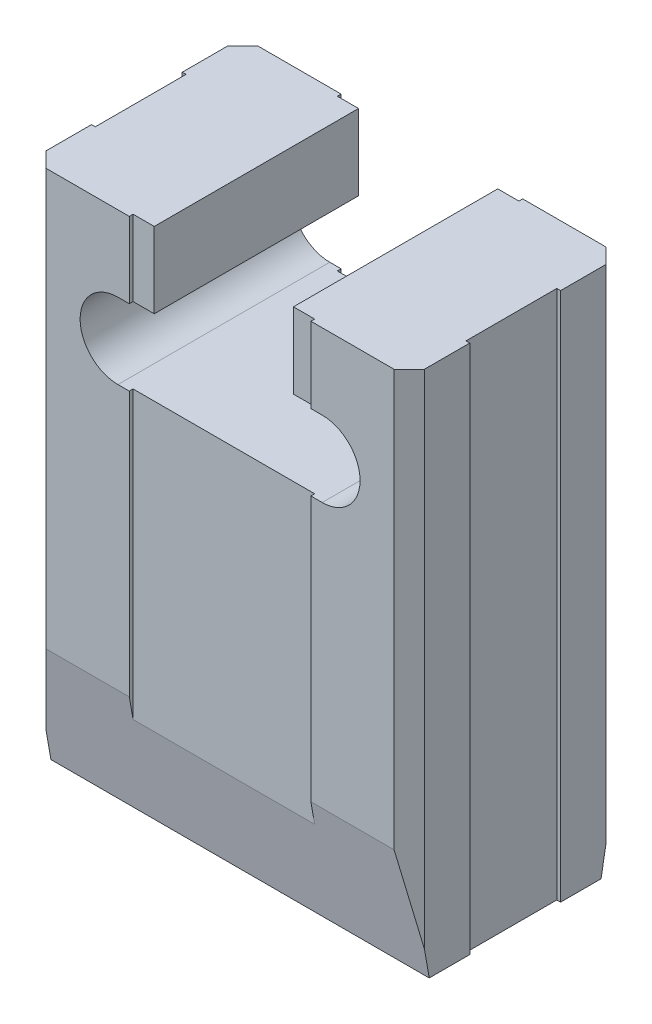
SolidWorks part; units mm, degrees
ref_plane "前基準面" through (0, 0, 0) normal (0, 0, 1) x (1, 0, 0)
ref_plane "上基準面" through (0, 0, 0) normal (0, 1, 0) x (1, 0, 0)
ref_plane "右基準面" through (0, 0, 0) normal (1, 0, 0) x (0, 0, -1)
sketch "草圖1" plane through (0, 0, 0) normal (0, 0, 1) x (1, 0, 0)
  line L0 (-25, -35) -> (25, 35) construction
  line L1 (-25, 35) -> (25, 35)
  line L2 (-25, 35) -> (-25, -35)
  line L3 (-25, -35) -> (25, -35)
  line L4 (25, 35) -> (25, -35)
  dimension "D1" = 50
  dimension "D2" = 70
extrude "伸長1" add sketch "草圖1" along normal blind 28
sketch "草圖4" plane through (0, 0, 28) normal (0, 0, 1) x (1, 0, 0)
  line L0 (-9.2, 35) -> (-9.2, 25)
  line L1 (25, 35) -> (-25, 35) construction
  line L2 (-9.2, 25) -> (-13.5, 25)
  line L4 (-13.5, 15) -> (13.5, 15)
  line L6 (13.5, 25) -> (9.2, 25)
  line L7 (9.2, 25) -> (9.2, 35)
  line L8 (9.2, 35) -> (-9.2, 35)
  line L9 (0, 0) -> (0, -35) construction
  line L10 (-25, -35) -> (25, -35) construction
  arc A0 (-13.5, 25) -> (-13.5, 15) centre (-13.5, 20) ccw
  arc A1 (13.5, 25) -> (13.5, 15) centre (13.5, 20) cw
  dimension "D2" = 10
  dimension "D1" = 10
  dimension "D3" = 18.4
  dimension "D4" = 27
extrude "除料-伸長6" cut sketch "草圖4" against normal through all
chamfer "導角1" distance 15 angle 10 1 edges at (0, -35, 0)
chamfer "導角2" distance 15 angle 10 1 edges at (0, -35, 28)
sketch "草圖6" plane through (0, 35, 0) normal (0, 1, 0) x (1, 0, 0)
  line L0 (-13.5, -28) -> (13.5, -28) construction
  line L1 (-12, -28) -> (12, -28)
  line L2 (-12, -28) -> (-12, -27.5)
  line L3 (-12, -27.5) -> (12, -27.5)
  line L4 (12, -28) -> (12, -27.5)
  line L5 (0, 0) -> (0, -28) construction
  line L6 (-9.2, 0) -> (-25, 0) construction
  line L7 (-12, 0) -> (12, 0)
  line L8 (-12, 0) -> (-12, -0.5)
  line L9 (-12, -0.5) -> (12, -0.5)
  line L10 (12, 0) -> (12, -0.5)
  dimension "D1" = 0.5
  dimension "D2" = 24
  dimension "D3" = 0.5
  dimension "D4" = 24
extrude "除料-伸長7" cut sketch "草圖6" against normal through all
sketch "草圖7" plane through (0, 35, 0) normal (0, 1, 0) x (1, 0, 0)
  line L0 (-25, -28) -> (-25, 0) construction
  line L1 (-25, -8) -> (-24.5, -8)
  line L2 (-25, -8) -> (-25, -20)
  line L3 (-25, -20) -> (-24.5, -20)
  line L4 (-24.5, -8) -> (-24.5, -20)
  line L5 (-9.2, -14) -> (-16.9898, -14) construction
  line L6 (-9.2, -0.5) -> (-9.2, -27.5) construction
  line L7 (25, -28) -> (25, 0) construction
  line L8 (25, -8) -> (24.5, -8)
  line L9 (25, -8) -> (25, -20)
  line L10 (25, -20) -> (24.5, -20)
  line L11 (24.5, -8) -> (24.5, -20)
  dimension "D1" = 12
  dimension "D2" = 0.5
  dimension "D3" = 0.5
  dimension "D4" = 12
extrude "除料-伸長8" cut sketch "草圖7" against normal through all
chamfer "導角3" distance 2 angle 45 4 edges at (25, 7.5, 0) (25, 7.5, 28) (-25, 7.5, 28) (-25, 7.5, 0)
